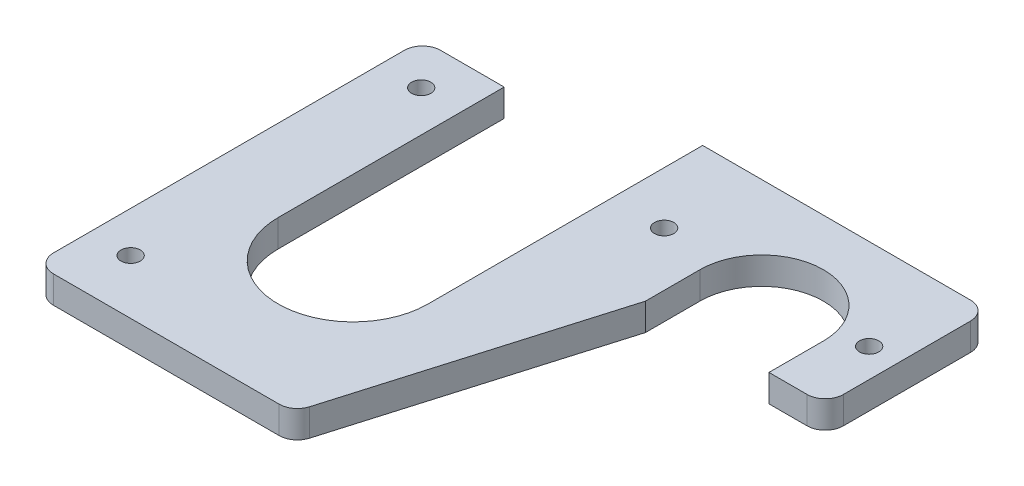
SolidWorks part; units mm, degrees
material "PC High Viscosity"
ref_plane "Front Plane" through (0, 0, 0) normal (0, 0, 1) x (1, 0, 0)
ref_plane "Top Plane" through (0, 0, 0) normal (0, 1, 0) x (1, 0, 0)
ref_plane "Right Plane" through (0, 0, 0) normal (1, 0, 0) x (0, 0, -1)
sketch "Sketch1" plane through (0, 0, 0) normal (0, 1, 0) x (1, 0, 0)
  line L0 (28.575, 81.7563) -> (28.575, 160.782)
  line L1 (0, 0) -> (180.975, 0) construction
  line L2 (0, 0) -> (0, 160.782) construction
  line L3 (28.575, 177.8) -> (180.975, 177.8) construction
  line L4 (180.975, 0) -> (180.975, 177.8) construction
  line L6 (0, 160.782) -> (0, 0)
  line L7 (0, 0) -> (82.55, 0)
  line L9 (80.9625, 81.7563) -> (80.9625, 177.8)
  line L10 (80.9625, 177.8) -> (121.7041, 177.8)
  line L13 (180.975, 139.7) -> (180.975, 177.8)
  line L14 (180.975, 177.8) -> (121.7041, 177.8)
  line L16 (118.11, 139.7) -> (118.11, 120.65)
  line L17 (82.55, 0) -> (118.11, 120.65)
  line L18 (161.29, 139.7) -> (161.29, 120.65)
  line L19 (180.975, 139.7) -> (180.975, 120.65)
  line L20 (180.975, 120.65) -> (161.29, 120.65)
  line L21 (0, 160.782) -> (28.575, 160.782)
  arc A0 (161.29, 139.7) -> (118.11, 139.7) centre (139.7, 139.7) ccw
  arc A1 (28.575, 81.7563) -> (80.9625, 81.7563) centre (54.7687, 81.7563) ccw
  dimension "D3" = 43.18
  dimension "D5" = 52.3875
  dimension "D1" = 177.8
  dimension "D2" = 180.975
  dimension "D4" = 38.1
  dimension "D6" = 81.7563
  dimension "D7" = 54.7687
  dimension "D8" = 139.7
  dimension "D9" = 19.05
  dimension "D10" = 82.55
  dimension "D11" = 121.7041
  dimension "D12" = 160.782
extrude "Boss-Extrude1" add sketch "Sketch1" along normal blind 9.525
sketch "Sketch2" plane through (0, 9.525, 0) normal (0, 1, 0) x (1, 0, 0)
  line L1 (0, 0) -> (94.3317, 0)
  line L2 (0, 0) -> (0, 25.4)
  line L3 (0, 25.4) -> (94.3317, 25.4)
  line L4 (94.3317, 0) -> (94.3317, 25.4)
  dimension "D1" = 25.4
extrude "Cut-Extrude1" cut sketch "Sketch2" against normal through all
fillet "Fillet1" radius 6.35 1 edges at (0, 4.7625, -25.4)
fillet "Fillet2" radius 6.35 4 edges at (0, 4.7625, -160.782) (180.975, 4.7625, -177.8) (180.975, 4.7625, -120.65) (90.0363, 4.7625, -25.4)
hole_wizard "1/4 Clearance Hole1" positions "Sketch3" profile "Sketch4" hole size "1/4" standard "ANSI Inch" end condition through all
sketch "Sketch3" plane through (0, 9.525, 0) normal (0, 1, 0) x (1, 0, 0)
  line L1 (28.575, 160.782) -> (6.35, 160.782) construction
  line L4 (161.29, 120.65) -> (174.625, 120.65) construction
  line L10 (99.2378, 131.2063) -> (99.2378, 177.8) construction
  line L11 (174.625, 177.8) -> (80.9625, 177.8) construction
  line L13 (17.4625, 95.25) -> (5.6328, 95.25) construction
  line L15 (0, 154.432) -> (0, 31.75) construction
  line L20 (170.9229, 130.175) -> (170.9229, 177.8) construction
  line L21 (174.625, 177.8) -> (80.9625, 177.8) construction
  line L24 (28.575, 118.8041) -> (0, 118.8041) construction
  line L25 (28.575, 81.7563) -> (28.575, 160.782) construction
  line L27 (14.2875, 118.8041) -> (14.2875, 63.4643) construction
  line L29 (118.11, 120.65) -> (118.11, 139.7) construction
  line L30 (180.975, 127) -> (180.975, 171.45) construction
  point P0 (14.2875, 146.05)
  point P2 (14.2875, 44.45)
  point P4 (99.2378, 146.05)
  point P6 (170.9229, 146.05)
  dimension "D1" = 25.4
  dimension "D2" = 14.732
  dimension "D3" = 18.8722
  dimension "D4" = 10.052
  dimension "D5" = 101.6
sketch "Sketch4" plane through (14.2875, 9.525, -146.05) normal (1, 0, 0) x (0, 0, 1)
  line L0 (0, 0) -> (0, 9.525)
  line L1 (0, 9.525) -> (3.3782, 9.525)
  line L2 (3.3782, 9.525) -> (3.3782, 0)
  line L5 (3.3782, 0) -> (0, 0)
  line L11 (0, -6.35) -> (0, 107.95) construction
  dimension "Thru Hole Dia." = 6.7564
  dimension "Thru Hole Depth" = 9.525
sketch "Sketch5" [suppressed] plane through (0, 9.525, 0) normal (0, 1, 0) x (1, 0, 0)
  line L0 (161.29, 133.35) -> (180.975, 133.35)
  line L1 (161.29, 139.7) -> (161.29, 120.65) construction
  line L2 (180.975, 127) -> (180.975, 171.45) construction
  line L3 (161.29, 133.35) -> (161.29, 120.65)
  line L4 (161.29, 120.65) -> (180.975, 120.65)
  line L5 (180.975, 120.65) -> (180.975, 133.35)
  line L6 (161.29, 120.65) -> (174.625, 120.65) construction
  circle A0 centre (170.9229, 146.05) radius 3.3782 construction
  dimension "D1" = 12.7
extrude "Cut-Extrude2" [suppressed] cut sketch "Sketch5" against normal through all
fillet "Fillet3" [suppressed] radius 6.35
sketch "Sketch6" [suppressed] plane through (0, 9.525, 0) normal (0, 1, 0) x (1, 0, 0)
  line L0 (26.4861, 81.7563) -> (26.4861, 177.8)
  line L1 (26.4861, 177.8) -> (83.0514, 177.8)
  line L2 (83.0514, 177.8) -> (83.0514, 81.7563)
  line L3 (174.625, 177.8) -> (80.9625, 177.8) construction
  arc A0 (26.4861, 81.7563) -> (83.0514, 81.7563) centre (54.7687, 81.7563) ccw
extrude "Cut-Extrude3" [suppressed] cut sketch "Sketch6" against normal through all
fillet "Fillet4" [suppressed] radius 12.7
chamfer "Chamfer1" [suppressed] distance 12.7 angle 45
fillet "Fillet5" [suppressed] radius 6.35
